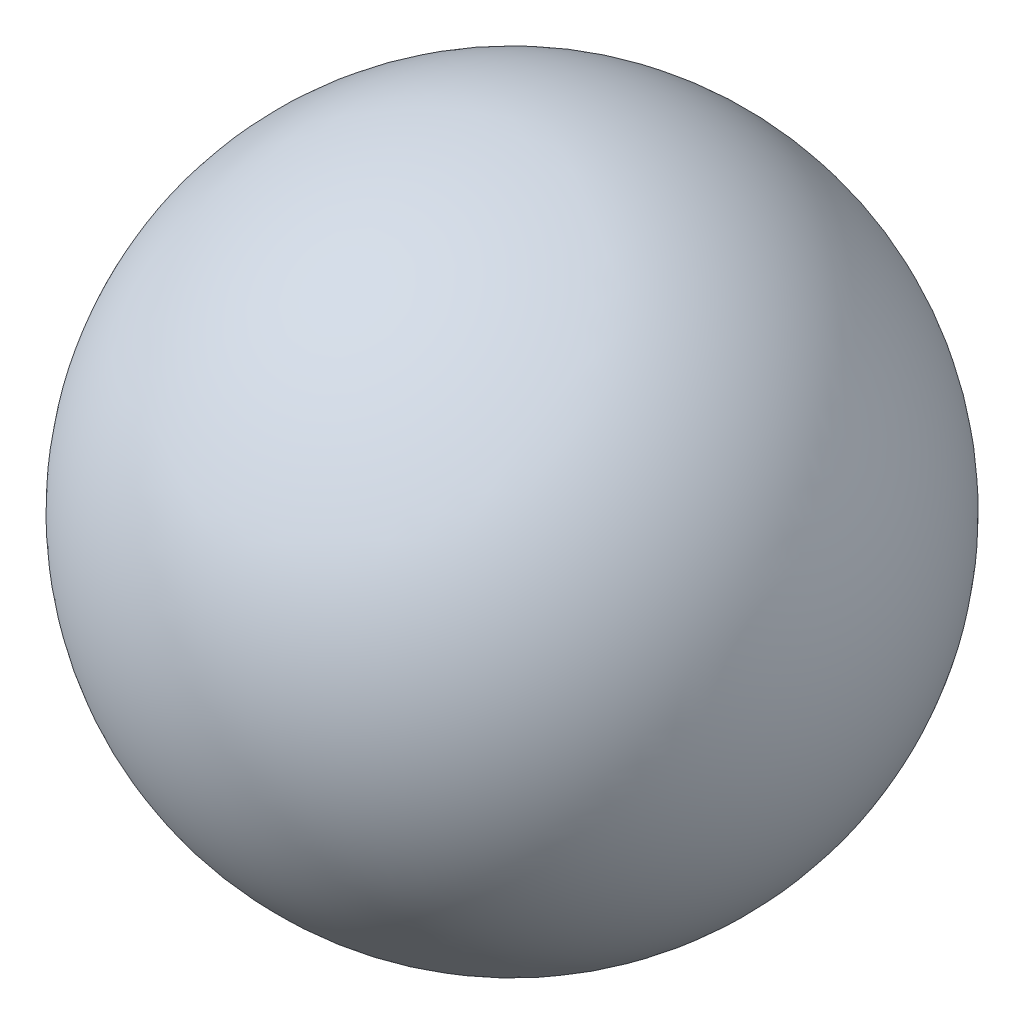
SolidWorks part; units mm, degrees
ref_plane "Piano frontale" through (0, 0, 0) normal (0, 0, 1) x (1, 0, 0)
ref_plane "Piano superiore" through (0, 0, 0) normal (0, 1, 0) x (1, 0, 0)
ref_plane "Piano destro" through (0, 0, 0) normal (1, 0, 0) x (0, 0, -1)
sketch "Schizzo1" plane through (0, 0, 0) normal (0, 0, 1) x (1, 0, 0)
  line L0 (-17, 0) -> (17, 0)
  arc A0 (17, 0) -> (-17, 0) centre (0, 0) ccw
ref_axis "Assi1" through (18.7, 0, 0) along (-1, 0, 0)
revolve "Rivoluzione5" add sketch "Schizzo1" angle 360 about axis through (18.7, 0, 0) along (-1, 0, 0)
